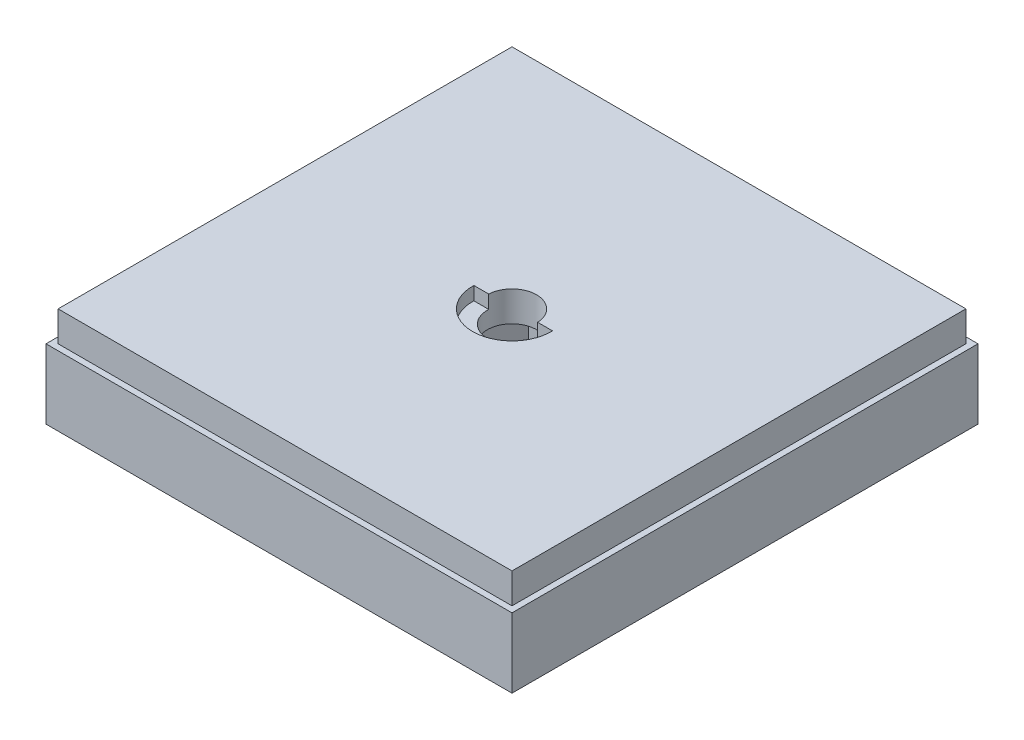
SolidWorks part; units mm, degrees
ref_plane "Front Plane" through (0, 0, 0) normal (0, 0, 1) x (1, 0, 0)
ref_plane "Top Plane" through (0, 0, 0) normal (0, 1, 0) x (1, 0, 0)
ref_plane "Right Plane" through (0, 0, 0) normal (1, 0, 0) x (0, 0, -1)
sketch "Sketch1" plane through (0, 0, 0) normal (0, 1, 0) x (1, 0, 0)
  line L0 (-77, 77) -> (0, 0) construction
  line L1 (-77, 77) -> (0, 77)
  line L2 (-77, 77) -> (-77, 0)
  line L3 (-77, 0) -> (0, 0)
  line L4 (0, 77) -> (0, 0)
  line L6 (-30.9944, 38.5) -> (-34.7472, 45)
  line L7 (-34.7472, 45) -> (-42.2528, 45)
  line L8 (-42.2528, 45) -> (-46.0056, 38.5)
  line L9 (-46.0056, 38.5) -> (-42.2528, 32)
  line L10 (-42.2528, 32) -> (-34.7472, 32)
  line L11 (-34.7472, 32) -> (-30.9944, 38.5)
  circle A0 centre (-38.5, 38.5) radius 6.5 construction
  dimension "D1" = 77
  dimension "D2" = 77
  dimension "D3" = 13
extrude "Boss-Extrude1" add sketch "Sketch1" along normal blind 11.5
sketch "Sketch2" plane through (0, 11.5, 0) normal (0, 1, 0) x (1, 0, 0)
  line L4 (-76, 76) -> (-1, 1) construction
  line L8 (-76, 76) -> (-76, 1)
  line L9 (-76, 1) -> (-1, 1)
  line L10 (-1, 1) -> (-1, 76)
  line L11 (-1, 76) -> (-76, 76)
  line L12 (-76, 76) -> (-76, 1)
  line L13 (-76, 1) -> (-1, 1)
  line L14 (-1, 1) -> (-1, 76)
  line L15 (-1, 76) -> (-76, 76)
  circle A0 centre (-38.5, 38.5) radius 4.05
  dimension "8.1" = 8.1
  dimension "D1" = 1
extrude "Boss-Extrude2" add sketch "Sketch2" along normal blind 5
sketch "Sketch3" plane through (0, 0, 0) normal (0, -1, 0) x (1, 0, 0)
  circle A0 centre (-38.5, -38.5) radius 8
  dimension "D1" = 16
extrude "Cut-Extrude1" cut sketch "Sketch3" against normal blind 7
sketch "Sketch4" plane through (0, 16.5, 0) normal (0, 1, 0) x (1, 0, 0)
  line L0 (-32.5, 38.5) -> (-19.5, 38.5) construction
  line L1 (-44.9969, 38.7) -> (-32.0031, 38.7)
  arc A0 (-44.9969, 38.7) -> (-32.0031, 38.7) centre (-38.5, 38.5) ccw
  dimension "D1" = 13
  dimension "D2" = 0.2
extrude "Cut-Extrude2" cut sketch "Sketch4" against normal blind 2.2
